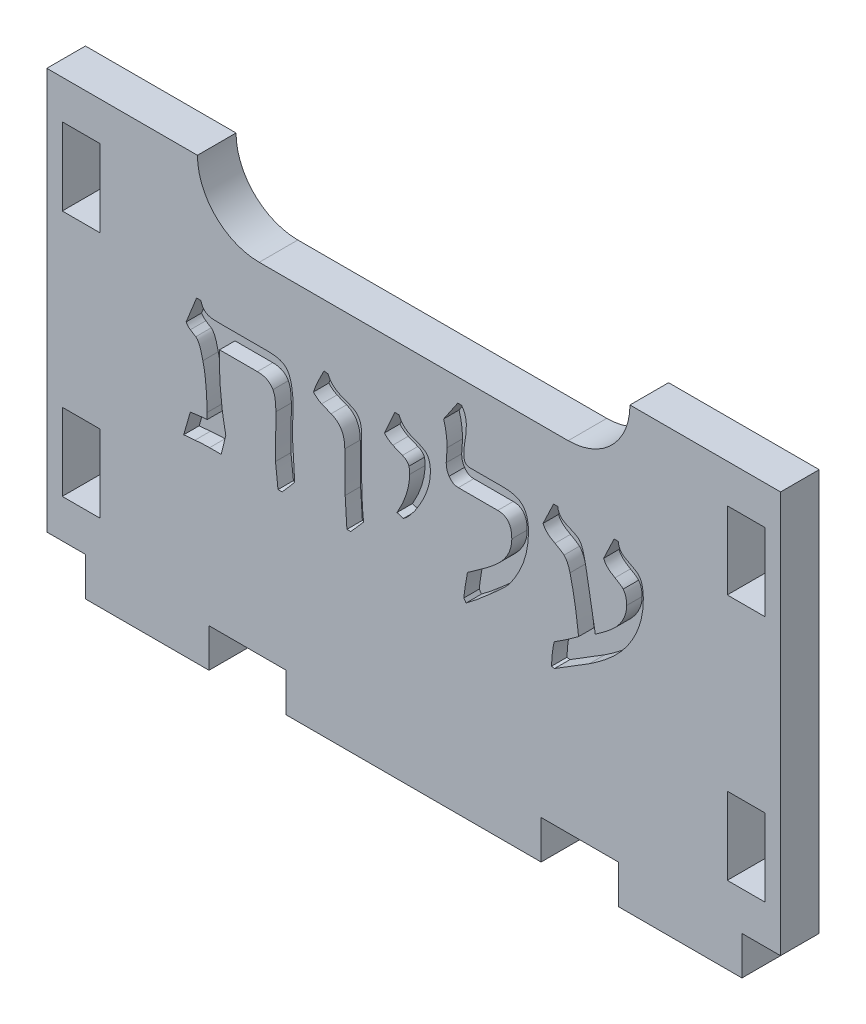
SolidWorks part; units mm, degrees
ref_plane "Front Plane" through (0, 0, 0) normal (0, 0, 1) x (1, 0, 0)
ref_plane "Top Plane" through (0, 0, 0) normal (0, 1, 0) x (1, 0, 0)
ref_plane "Right Plane" through (0, 0, 0) normal (1, 0, 0) x (0, 0, -1)
sketch "Sketch1" plane through (0, 0, 0) normal (0, 0, 1) x (1, 0, 0)
  line L0 (0, 0) -> (0, 66.04)
  line L1 (0, 66.04) -> (-120.65, 66.04)
  line L2 (-120.65, 66.04) -> (-120.65, 0)
  line L14 (-120.65, 0) -> (0, 0)
  dimension "D2" = 66.04
  dimension "D3" = 120.65
extrude "Boss-Extrude1" add sketch "Sketch1" along normal blind 6.35
sketch "Sketch2" plane through (0, 0, 6.35) normal (0, 0, 1) x (1, 0, 0)
  line L0 (-120.65, 33.02) -> (0, 33.02) construction
  line L9 (-118.11, 6.35) -> (-111.887, 6.35)
  line L10 (-118.11, 6.35) -> (-118.11, 19.05)
  line L11 (-118.11, 19.05) -> (-111.887, 19.05)
  line L12 (-111.887, 6.35) -> (-111.887, 19.05)
  line L17 (-120.65, 66.04) -> (-120.65, 0) construction
  line L18 (0, 0) -> (0, 66.04) construction
  line L19 (-60.325, 66.04) -> (-60.325, 0) construction
  line L20 (0, 66.04) -> (-120.65, 66.04) construction
  line L22 (-118.11, 46.99) -> (-111.887, 46.99)
  line L23 (-111.887, 59.69) -> (-111.887, 46.99)
  line L24 (-118.11, 59.69) -> (-111.887, 59.69)
  line L25 (-118.11, 59.69) -> (-118.11, 46.99)
  line L27 (-2.54, 59.69) -> (-2.54, 46.99)
  line L28 (-2.54, 59.69) -> (-8.763, 59.69)
  line L29 (-8.763, 59.69) -> (-8.763, 46.99)
  line L30 (-2.54, 46.99) -> (-8.763, 46.99)
  line L31 (-2.54, 19.05) -> (-8.763, 19.05)
  line L32 (-8.763, 6.35) -> (-8.763, 19.05)
  line L33 (-2.54, 6.35) -> (-8.763, 6.35)
  line L34 (-2.54, 6.35) -> (-2.54, 19.05)
  line L35 (-120.65, 0) -> (0, 0) construction
  dimension "D1" = 6.223
  dimension "D2" = 12.7
  dimension "D3" = 6.35
  dimension "D4" = 2.54
extrude "Cut-Extrude1" cut sketch "Sketch2" against normal up to next
sketch "Sketch4" plane through (0, 0, 0) normal (0, -1, 0) x (1, 0, 0)
  line L0 (0, 6.35) -> (0, 0) construction
  line L5 (-60.325, 6.35) -> (-60.325, 0) construction
  line L6 (-114.3, 6.35) -> (-114.3, 0)
  line L8 (-81.28, 6.35) -> (-81.28, 0)
  line L11 (-114.3, 6.35) -> (-93.98, 6.35)
  line L12 (-39.37, 6.35) -> (-39.37, 0)
  line L13 (-93.98, 6.35) -> (-93.98, 0)
  line L14 (-81.28, 6.35) -> (-39.37, 6.35)
  line L15 (-114.3, 0) -> (-93.98, 0)
  line L19 (-6.35, 0) -> (-26.67, 0)
  line L20 (-26.67, 6.35) -> (-26.67, 0)
  line L21 (-6.35, 6.35) -> (-26.67, 6.35)
  line L22 (-6.35, 6.35) -> (-6.35, 0)
  line L23 (-39.37, 0) -> (-81.28, 0)
  line L24 (-120.65, 6.35) -> (0, 6.35) construction
  line L25 (-120.65, 6.35) -> (0, 6.35) construction
  line L26 (-120.65, 0) -> (0, 0) construction
  line L28 (-120.65, 6.35) -> (-120.65, 0) construction
  dimension "D1" = 12.7
  dimension "D2" = 6.35
  dimension "D3" = 20.955
  dimension "D4" = 6.35
extrude "Boss-Extrude2" add sketch "Sketch4" along normal blind 6.35
sketch "Sketch5" plane through (0, 0, 6.35) normal (0, 0, 1) x (1, 0, 0)
  line L0 (-120.65, 25.4) -> (0, 25.4) construction
  line L3 (-39.37, -6.35) -> (-81.28, -6.35) construction
  text T0 "עליות" font "Narkisim" height 25.4
  dimension "D1" = 31.75
extrude "Cut-Extrude2" cut sketch "Sketch5" against normal blind 2.54
sketch "Sketch7" plane through (0, 0, 6.35) normal (0, 0, 1) x (1, 0, 0)
  line L0 (-85.725, 66.04) -> (-34.925, 66.04) construction
  line L1 (0, 66.04) -> (-120.65, 66.04) construction
  line L2 (-85.725, 76.2) -> (-34.925, 76.2)
  line L3 (-85.725, 55.88) -> (-34.925, 55.88)
  arc A0 (-85.725, 76.2) -> (-85.725, 55.88) centre (-85.725, 66.04) ccw
  arc A1 (-34.925, 55.88) -> (-34.925, 76.2) centre (-34.925, 66.04) ccw
  point P4 (-60.325, 66.04)
  dimension "D2" = 10.16
  dimension "D1" = 50.8
extrude "Cut-Extrude3" cut sketch "Sketch7" against normal through all
